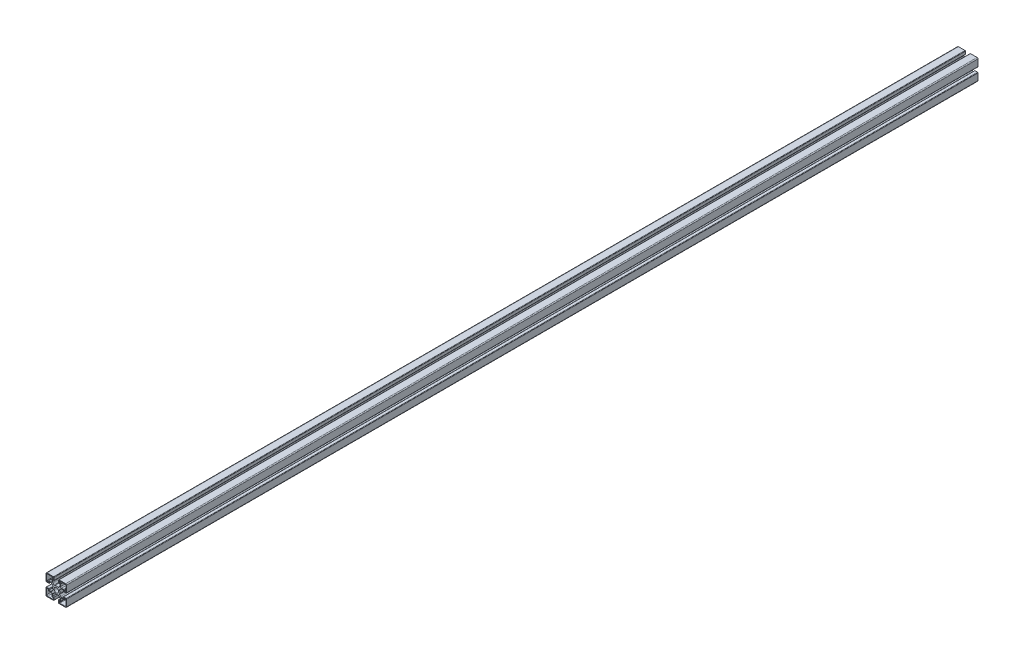
SolidWorks part; units mm, degrees
ref_plane "Front Plane" through (0, 0, 0) normal (0, 0, 1) x (1, 0, 0)
ref_plane "Top Plane" through (0, 0, 0) normal (0, 1, 0) x (1, 0, 0)
ref_plane "Right Plane" through (0, 0, 0) normal (1, 0, 0) x (0, 0, -1)
sketch "Sketch1" plane through (0, 0, 0) normal (0, 0, 1) x (1, 0, 0)
  line L0 (-5, -15.7059) -> (-8, -15.7059)
  line L1 (-20.5, -22.5) -> (-6, -22.5)
  line L2 (-22.5, -20.5) -> (-22.5, -6)
  line L5 (-21.9142, -21.9142) -> (22.5, 22.5) construction
  line L6 (-22.5, 22.5) -> (22.5, -22.5) construction
  line L7 (-20.5, -22.5) -> (-6, -22.5)
  line L8 (-22.5, -20.5) -> (-22.5, -6)
  line L10 (-5, -21.5) -> (-5, -15.7059)
  line L11 (-8, -15.7059) -> (-8, -11.9485)
  line L12 (-7.1213, -9.8272) -> (-4.6684, -7.3742)
  line L14 (-19, -21) -> (-7.5, -21)
  line L15 (-6.5, -20) -> (-6.5, -18.2059)
  line L16 (-7.5, -17.2059) -> (-8.5, -17.2059)
  line L17 (-9.5, -16.2059) -> (-9.5, -11.5)
  line L18 (-16.2059, -9.5) -> (-11.5, -9.5)
  line L19 (-17.2059, -7.5) -> (-17.2059, -8.5)
  line L20 (-20, -6.5) -> (-18.2059, -6.5)
  line L21 (-21, -19) -> (-21, -7.5)
  line L22 (-9.8272, -7.1213) -> (-7.3742, -4.6684)
  line L23 (-15.7059, -8) -> (-11.9485, -8)
  line L24 (-15.7059, -5) -> (-15.7059, -8)
  line L25 (-21.5, -5) -> (-15.7059, -5)
  line L26 (0, 27.7778) -> (0, -29.5537) construction
  line L27 (-31.2741, 0) -> (30.8136, 0) construction
  line L28 (-9.5, 16.2059) -> (-9.5, 11.5)
  line L29 (-16.2059, 9.5) -> (-11.5, 9.5)
  line L30 (-17.2059, 7.5) -> (-17.2059, 8.5)
  line L31 (-20, 6.5) -> (-18.2059, 6.5)
  line L32 (-21, 19) -> (-21, 7.5)
  line L33 (-19, 21) -> (-7.5, 21)
  line L34 (-6.5, 20) -> (-6.5, 18.2059)
  line L35 (-7.5, 17.2059) -> (-8.5, 17.2059)
  line L36 (-22.5, 20.5) -> (-22.5, 6)
  line L37 (-20.5, 22.5) -> (-6, 22.5)
  line L38 (-5, 21.5) -> (-5, 15.7059)
  line L39 (-5, 15.7059) -> (-8, 15.7059)
  line L40 (-8, 15.7059) -> (-8, 11.9485)
  line L41 (-7.1213, 9.8272) -> (-4.6684, 7.3742)
  line L42 (-9.8272, 7.1213) -> (-7.3742, 4.6684)
  line L43 (-15.7059, 8) -> (-11.9485, 8)
  line L44 (-15.7059, 5) -> (-15.7059, 8)
  line L45 (-21.5, 5) -> (-15.7059, 5)
  line L46 (16.2059, 9.5) -> (11.5, 9.5)
  line L47 (9.5, 16.2059) -> (9.5, 11.5)
  line L48 (7.5, 17.2059) -> (8.5, 17.2059)
  line L49 (6.5, 20) -> (6.5, 18.2059)
  line L50 (19, 21) -> (7.5, 21)
  line L51 (21, 19) -> (21, 7.5)
  line L52 (20, 6.5) -> (18.2059, 6.5)
  line L53 (17.2059, 7.5) -> (17.2059, 8.5)
  line L54 (20.5, 22.5) -> (6, 22.5)
  line L55 (22.5, 20.5) -> (22.5, 6)
  line L56 (21.5, 5) -> (15.7059, 5)
  line L57 (15.7059, 5) -> (15.7059, 8)
  line L58 (15.7059, 8) -> (11.9485, 8)
  line L59 (9.8272, 7.1213) -> (7.3742, 4.6684)
  line L60 (7.1213, 9.8272) -> (4.6684, 7.3742)
  line L61 (8, 15.7059) -> (8, 11.9485)
  line L62 (5, 15.7059) -> (8, 15.7059)
  line L63 (5, 21.5) -> (5, 15.7059)
  line L64 (9.5, -16.2059) -> (9.5, -11.5)
  line L65 (16.2059, -9.5) -> (11.5, -9.5)
  line L66 (17.2059, -7.5) -> (17.2059, -8.5)
  line L67 (20, -6.5) -> (18.2059, -6.5)
  line L68 (21, -19) -> (21, -7.5)
  line L69 (19, -21) -> (7.5, -21)
  line L70 (6.5, -20) -> (6.5, -18.2059)
  line L71 (7.5, -17.2059) -> (8.5, -17.2059)
  line L72 (22.5, -20.5) -> (22.5, -6)
  line L73 (20.5, -22.5) -> (6, -22.5)
  line L74 (5, -21.5) -> (5, -15.7059)
  line L75 (5, -15.7059) -> (8, -15.7059)
  line L76 (8, -15.7059) -> (8, -11.9485)
  line L77 (7.1213, -9.8272) -> (4.6684, -7.3742)
  line L78 (9.8272, -7.1213) -> (7.3742, -4.6684)
  line L79 (15.7059, -8) -> (11.9485, -8)
  line L80 (15.7059, -5) -> (15.7059, -8)
  line L81 (21.5, -5) -> (15.7059, -5)
  circle A0 centre (0, 0) radius 5
  arc A1 (-3.5211, -7.1834) -> (3.5211, -7.1834) centre (0, 0) ccw
  arc A2 (-3.5211, -7.1834) -> (-4.6684, -7.3742) centre (-3.9613, -8.0814) ccw
  arc A3 (-8, -11.9485) -> (-7.1213, -9.8272) centre (-5, -11.9485) cw
  arc A4 (-6, -22.5) -> (-5, -21.5) centre (-6, -21.5) ccw
  arc A5 (-8.5, -17.2059) -> (-9.5, -16.2059) centre (-8.5, -16.2059) cw
  arc A6 (-6.5, -18.2059) -> (-7.5, -17.2059) centre (-7.5, -18.2059) ccw
  arc A7 (-6.5, -20) -> (-7.5, -21) centre (-7.5, -20) cw
  arc A8 (-17.2059, -8.5) -> (-16.2059, -9.5) centre (-16.2059, -8.5) ccw
  arc A9 (-18.2059, -6.5) -> (-17.2059, -7.5) centre (-18.2059, -7.5) cw
  arc A10 (-20, -6.5) -> (-21, -7.5) centre (-20, -7.5) ccw
  arc A11 (-22.5, -20.5) -> (-20.5, -22.5) centre (-20.5, -20.5) ccw
  arc A12 (-9.5, -11.5) -> (-11.5, -9.5) centre (-11.5, -11.5) ccw
  arc A13 (-19, -21) -> (-21, -19) centre (-19, -19) cw
  arc A14 (-7.1834, -3.5211) -> (-7.3742, -4.6684) centre (-8.0814, -3.9613) cw
  arc A15 (-11.9485, -8) -> (-9.8272, -7.1213) centre (-11.9485, -5) ccw
  arc A16 (-22.5, -6) -> (-21.5, -5) centre (-21.5, -6) cw
  arc A17 (-11.5, 9.5) -> (-9.5, 11.5) centre (-11.5, 11.5) ccw
  arc A18 (-17.2059, 8.5) -> (-16.2059, 9.5) centre (-16.2059, 8.5) cw
  arc A19 (-18.2059, 6.5) -> (-17.2059, 7.5) centre (-18.2059, 7.5) ccw
  arc A20 (-20, 6.5) -> (-21, 7.5) centre (-20, 7.5) cw
  arc A21 (-21, 19) -> (-19, 21) centre (-19, 19) cw
  arc A22 (-6.5, 20) -> (-7.5, 21) centre (-7.5, 20) ccw
  arc A23 (-6.5, 18.2059) -> (-7.5, 17.2059) centre (-7.5, 18.2059) cw
  arc A24 (-8.5, 17.2059) -> (-9.5, 16.2059) centre (-8.5, 16.2059) ccw
  arc A25 (-20.5, 22.5) -> (-22.5, 20.5) centre (-20.5, 20.5) ccw
  arc A26 (-6, 22.5) -> (-5, 21.5) centre (-6, 21.5) cw
  arc A27 (-8, 11.9485) -> (-7.1213, 9.8272) centre (-5, 11.9485) ccw
  arc A28 (-3.5211, 7.1834) -> (-4.6684, 7.3742) centre (-3.9613, 8.0814) cw
  arc A29 (-7.1834, 3.5211) -> (-7.3742, 4.6684) centre (-8.0814, 3.9613) ccw
  arc A30 (-11.9485, 8) -> (-9.8272, 7.1213) centre (-11.9485, 5) cw
  arc A31 (-22.5, 6) -> (-21.5, 5) centre (-21.5, 6) ccw
  arc A32 (9.5, 11.5) -> (11.5, 9.5) centre (11.5, 11.5) ccw
  arc A33 (8.5, 17.2059) -> (9.5, 16.2059) centre (8.5, 16.2059) cw
  arc A34 (6.5, 18.2059) -> (7.5, 17.2059) centre (7.5, 18.2059) ccw
  arc A35 (6.5, 20) -> (7.5, 21) centre (7.5, 20) cw
  arc A36 (19, 21) -> (21, 19) centre (19, 19) cw
  arc A37 (20, 6.5) -> (21, 7.5) centre (20, 7.5) ccw
  arc A38 (18.2059, 6.5) -> (17.2059, 7.5) centre (18.2059, 7.5) cw
  arc A39 (17.2059, 8.5) -> (16.2059, 9.5) centre (16.2059, 8.5) ccw
  arc A40 (22.5, 20.5) -> (20.5, 22.5) centre (20.5, 20.5) ccw
  arc A41 (22.5, 6) -> (21.5, 5) centre (21.5, 6) cw
  arc A42 (11.9485, 8) -> (9.8272, 7.1213) centre (11.9485, 5) ccw
  arc A43 (7.1834, 3.5211) -> (7.3742, 4.6684) centre (8.0814, 3.9613) cw
  arc A44 (3.5211, 7.1834) -> (4.6684, 7.3742) centre (3.9613, 8.0814) ccw
  arc A45 (8, 11.9485) -> (7.1213, 9.8272) centre (5, 11.9485) cw
  arc A46 (6, 22.5) -> (5, 21.5) centre (6, 21.5) ccw
  arc A47 (11.5, -9.5) -> (9.5, -11.5) centre (11.5, -11.5) ccw
  arc A48 (17.2059, -8.5) -> (16.2059, -9.5) centre (16.2059, -8.5) cw
  arc A49 (18.2059, -6.5) -> (17.2059, -7.5) centre (18.2059, -7.5) ccw
  arc A50 (20, -6.5) -> (21, -7.5) centre (20, -7.5) cw
  arc A51 (21, -19) -> (19, -21) centre (19, -19) cw
  arc A52 (6.5, -20) -> (7.5, -21) centre (7.5, -20) ccw
  arc A53 (6.5, -18.2059) -> (7.5, -17.2059) centre (7.5, -18.2059) cw
  arc A54 (8.5, -17.2059) -> (9.5, -16.2059) centre (8.5, -16.2059) ccw
  arc A55 (20.5, -22.5) -> (22.5, -20.5) centre (20.5, -20.5) ccw
  arc A56 (6, -22.5) -> (5, -21.5) centre (6, -21.5) cw
  arc A57 (8, -11.9485) -> (7.1213, -9.8272) centre (5, -11.9485) ccw
  arc A58 (3.5211, -7.1834) -> (4.6684, -7.3742) centre (3.9613, -8.0814) cw
  arc A59 (7.1834, -3.5211) -> (7.3742, -4.6684) centre (8.0814, -3.9613) ccw
  arc A60 (11.9485, -8) -> (9.8272, -7.1213) centre (11.9485, -5) cw
  arc A61 (22.5, -6) -> (21.5, -5) centre (21.5, -6) ccw
  arc A62 (-7.1834, 3.5211) -> (-7.1834, -3.5211) centre (0, 0) ccw
  arc A63 (3.5211, 7.1834) -> (-3.5211, 7.1834) centre (0, 0) ccw
  arc A64 (7.1834, -3.5211) -> (7.1834, 3.5211) centre (0, 0) ccw
  point P0 (0, 0)
  point P19 (-8, -10.7059)
  point P48 (-9.5, -9.5)
  point P51 (-21, -21)
  point P214 (0, 0)
  dimension "D3" = 17.5
  dimension "D5" = 1
  dimension "D6" = 3
  dimension "D2" = 1
  dimension "D11" = 1
  dimension "D12" = 2
  dimension "D1" = 45
  dimension "D4" = 5
  dimension "D7" = 1.5
  dimension "D8" = 1.5
  dimension "D9" = 1.5
  dimension "D10" = 1.5
  dimension "D13" = 4
extrude "Boss-Extrude1" add sketch "Sketch1" along normal blind 2000 contours A59 A64 A43 L59 A42 L58 L57 L56 A41 L55 A40 L54 A46 L63 L62 L61 A45 L60 A44 A63 A28 L41 A27 L40 L39 L38 A26 L37 A25 L36 A31 L45 L44 L43 A30 L42 A29 A62 A14 L22 A15 L23 L24 L25 A16 L2 A11 L1 A4 L10 L0
